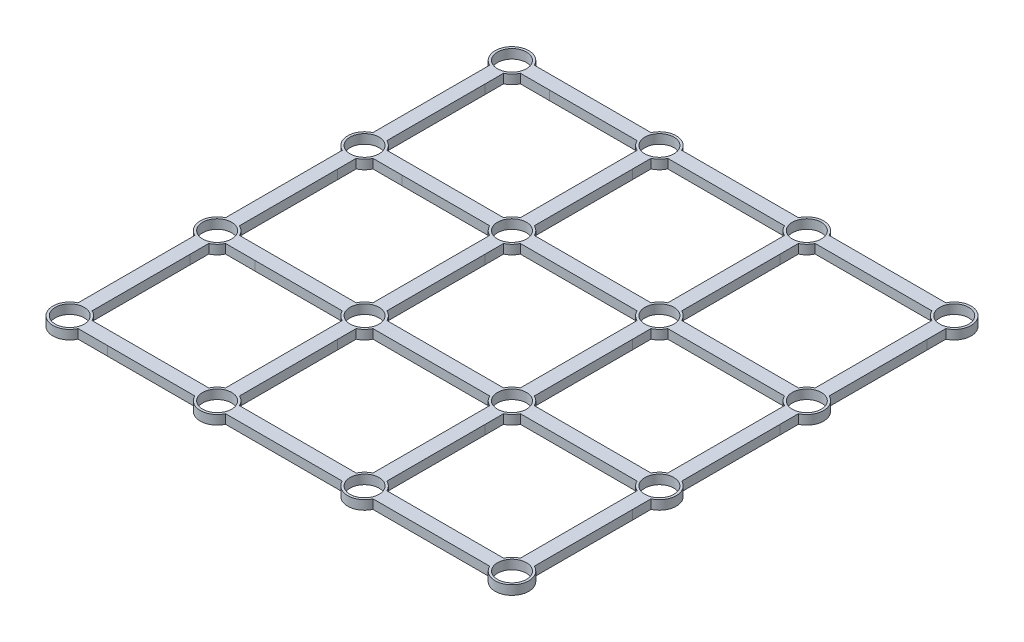
SolidWorks part; units mm, degrees
ref_plane "Front Plane" through (0, 0, 0) normal (0, 0, 1) x (1, 0, 0)
ref_plane "Top Plane" through (0, 0, 0) normal (0, 1, 0) x (1, 0, 0)
ref_plane "Right Plane" through (0, 0, 0) normal (1, 0, 0) x (0, 0, -1)
sketch "Sketch1" plane through (0, 0, 0) normal (0, 1, 0) x (1, 0, 0)
  line L0 (-35.5988, -39.5662) -> (-35.5988, -36.6288) construction
  line L1 (-38.0977, -38.0975) -> (38.1001, -38.0975) construction
  line L2 (-38.0977, -38.0975) -> (-38.098, -10.2001) construction
  line L3 (-15.2963, 38.0999) -> (38.1001, 38.0999) construction
  line L4 (38.1001, -38.0975) -> (38.1001, 38.0999) construction
  line L5 (-38.0977, -38.0975) -> (10.6495, 10.6495) construction
  line L6 (15.3401, -11.5) -> (35.4596, -11.4992)
  line L7 (-10.2, -39.5697) -> (-10.2, -37.3756) construction
  line L8 (15.2, -39.5697) -> (15.2, -39.3) construction
  line L9 (40.6, -39.5697) -> (40.6, -36.6303) construction
  line L10 (-36.8987, -35.9048) -> (-36.8987, -35.9073)
  line L11 (15.2, -14.1697) -> (15.2, -11.2303) construction
  line L12 (40.6, -14.1697) -> (40.6, -11.2303) construction
  line L13 (-10.2, 11.2303) -> (-10.2, 11.2305) construction
  line L14 (15.2, 11.2303) -> (15.2, 11.2305) construction
  line L15 (40.6, 11.2303) -> (40.6, 14.1697) construction
  line L16 (-36.901, 35.9049) -> (-36.901, 35.9064)
  line L17 (15.2, 36.6303) -> (15.2, 36.6305) construction
  line L18 (40.6, 36.6303) -> (40.6, 39.5697) construction
  line L19 (-35.6, -14.1697) -> (-35.6, -11.2303) construction
  line L20 (-35.6, 11.2303) -> (-35.6, 14.1697) construction
  line L21 (-35.6, 36.6303) -> (-35.6, 36.632) construction
  line L22 (-13.9013, 32.2466) -> (-13.8993, 35.4598)
  line L27 (-38.098, -9.7993) -> (-38.0985, 38.0988) construction
  line L28 (40.1506, 40.1506) -> (10.9323, 10.9323) construction
  line L29 (-11.4987, 32.2466) -> (-11.5007, 35.4597)
  line L30 (11.4987, 32.2466) -> (11.5007, 35.4598)
  line L31 (13.9013, 32.2466) -> (13.8993, 35.4598)
  line L32 (-30.4194, 38.0999) -> (-30.4194, 38.8938) construction
  line L37 (-30.4194, 38.0999) -> (-30.4194, 37.3063) construction
  line L38 (-30.4194, 38.0999) -> (-30.4194, 39.3) construction
  line L39 (-30.4194, 38.0999) -> (-30.4194, 36.9) construction
  line L40 (-30.4194, 39.3) -> (-35.4595, 39.2991)
  line L41 (-30.4194, 36.9) -> (-35.4604, 36.901)
  line L42 (-30.4194, 39.3) -> (-15.3399, 39.3)
  line L43 (-30.4194, 36.9) -> (-15.3399, 36.9)
  line L44 (-38.0985, 32.2466) -> (-36.8987, 32.2466) construction
  line L45 (-38.0985, 32.2466) -> (-39.3013, 32.2466) construction
  line L46 (-39.3013, 32.2466) -> (-39.2993, 35.4599)
  line L47 (-36.8987, 32.2466) -> (-36.9007, 35.4606)
  line L48 (-14.8932, 39.2999) -> (-10.5067, 39.3001) construction
  line L49 (-10.0599, 39.3001) -> (10.0599, 39.3001)
  line L50 (-14.8931, 36.9) -> (-10.5069, 36.9) construction
  line L51 (-10.5069, 36.9) -> (-10.5067, 36.9)
  line L52 (10.5069, 36.9) -> (14.8931, 36.9) construction
  line L53 (10.5068, 39.3001) -> (14.8933, 39.3001) construction
  line L55 (15.34, 36.9) -> (35.4597, 36.9)
  line L56 (0, 41) -> (0, -41) construction
  line L57 (-41, 0) -> (41, 0) construction
  line L58 (36.8987, 32.2466) -> (36.8999, 35.4597)
  line L59 (39.3013, 32.2466) -> (39.3003, 35.4598)
  line L60 (-39.3013, 32.2466) -> (-39.3013, 15.3396)
  line L61 (-36.8987, 32.2466) -> (-36.8987, 15.3396)
  line L62 (-13.9013, 32.2466) -> (-13.9013, 15.3397)
  line L63 (-11.4987, 32.2466) -> (-11.4987, 15.3397)
  line L64 (11.4987, 32.2466) -> (11.4987, 15.3397)
  line L65 (13.9013, 32.2466) -> (13.9013, 15.3397)
  line L66 (36.8987, 32.2466) -> (36.8987, 15.3401)
  line L67 (39.3013, 32.2466) -> (39.3013, 15.3401)
  line L68 (-30.4194, 13.9) -> (-35.4595, 13.8991)
  line L69 (-30.4194, 11.5) -> (-35.4596, 11.501)
  line L70 (-30.4194, 11.5) -> (-15.34, 11.5)
  line L71 (-30.4194, 13.9) -> (-15.3401, 13.9)
  line L72 (-10.0598, 13.9001) -> (10.0599, 13.9001)
  line L73 (-10.06, 11.5) -> (10.06, 11.5)
  line L74 (15.3402, 13.9001) -> (35.4593, 13.9001)
  line L75 (15.34, 11.5) -> (35.4591, 11.5)
  line L76 (-30.4194, -11.5) -> (-35.4601, -11.5009)
  line L77 (-30.4194, -13.9) -> (-35.4599, -13.899)
  line L78 (-30.4194, -13.9) -> (-15.3401, -13.9)
  line L79 (-30.4194, -11.5) -> (-15.3401, -11.5)
  line L80 (-10.06, -11.4999) -> (10.06, -11.4999)
  line L81 (-10.0599, -13.9) -> (10.0599, -13.9)
  line L83 (15.3401, -13.9) -> (35.4599, -13.9)
  line L84 (-30.4194, -36.9) -> (-35.4577, -36.9009)
  line L85 (-30.4194, -39.3) -> (-35.4599, -39.299)
  line L86 (-30.4194, -39.3) -> (-15.3404, -39.3)
  line L87 (-30.4194, -36.9) -> (-15.3405, -36.9)
  line L88 (-10.0595, -36.8999) -> (10.0595, -36.8999)
  line L89 (-10.0596, -39.3) -> (10.0597, -39.3)
  line L90 (15.3405, -36.8999) -> (35.4595, -36.8999)
  line L91 (15.3404, -39.3) -> (35.4599, -39.3)
  line L92 (-39.3013, 6.8466) -> (-39.3013, -10.0604)
  line L93 (-36.8987, 6.8466) -> (-36.8987, -10.0609)
  line L94 (-13.9013, 6.8466) -> (-13.9013, -10.0605)
  line L95 (-11.4987, 6.8466) -> (-11.4987, -10.0605)
  line L96 (11.4987, 6.8466) -> (11.4987, -10.0605)
  line L97 (13.9013, 6.8466) -> (13.9013, -10.0605)
  line L98 (36.8987, 6.8466) -> (36.8987, -10.0596)
  line L99 (39.3013, 6.8466) -> (39.3013, -10.0599)
  line L100 (-39.3013, 6.8466) -> (-39.2993, 10.0599)
  line L101 (-36.8987, 6.8466) -> (-36.9007, 10.0599)
  line L102 (-13.9013, 6.8466) -> (-13.8993, 10.0598)
  line L103 (-11.4987, 6.8466) -> (-11.5007, 10.0598)
  line L104 (11.4987, 6.8466) -> (11.5007, 10.0598)
  line L105 (13.9013, 6.8466) -> (13.8993, 10.0598)
  line L106 (36.8987, 6.8466) -> (36.8999, 10.0591)
  line L107 (39.3013, 6.8466) -> (39.3003, 10.0591)
  line L108 (-39.3013, -18.5534) -> (-39.3013, -35.4607)
  line L109 (-36.8987, -18.5534) -> (-36.8987, -35.4586)
  line L110 (-13.9013, -18.5534) -> (-13.9013, -35.4599)
  line L111 (-11.4987, -18.5534) -> (-11.4987, -35.4599)
  line L112 (11.4987, -18.5534) -> (11.4987, -35.4599)
  line L113 (13.9013, -18.5534) -> (13.9013, -35.4599)
  line L114 (36.8987, -18.5534) -> (36.8987, -35.4599)
  line L115 (39.3013, -18.5534) -> (39.3013, -35.4601)
  line L116 (-39.3013, -18.5534) -> (-39.2993, -15.3408)
  line L117 (-36.8987, -18.5534) -> (-36.9007, -15.3403)
  line L118 (-13.9013, -18.5534) -> (-13.8993, -15.3404)
  line L119 (-11.4987, -18.5534) -> (-11.5007, -15.3404)
  line L120 (11.4987, -18.5534) -> (11.5007, -15.3404)
  line L121 (13.9013, -18.5534) -> (13.8993, -15.3404)
  line L122 (36.8987, -18.5534) -> (36.8999, -15.3394)
  line L123 (39.3013, -18.5534) -> (39.3003, -15.339)
  line L124 (15.2, 13.9001) -> (15.2, 14.1697) construction
  line L125 (15.2, -36.8999) -> (15.2, -36.6303) construction
  line L126 (38.0998, -38.0995) -> (-41.0002, 41.0005) construction
  line L128 (-35.9036, -36.901) -> (-35.9061, -36.901)
  line L129 (15.2, 12.6828) -> (15.2, 12.7176) construction
  line L130 (10.9324, 10.9323) -> (38.1001, 38.0999) construction
  line L131 (10.6495, 10.6495) -> (-41, -41) construction
  line L132 (36.9001, 10.5063) -> (36.9001, 10.5067)
  line L133 (35.9064, 11.5) -> (35.9068, 11.5)
  line L134 (36.9001, 35.9063) -> (36.9001, 35.9067)
  line L135 (35.9065, 36.9) -> (35.9068, 36.9)
  line L136 (15.3401, 39.3001) -> (35.4599, 39.3001)
  line L137 (15.2, 38.0823) -> (15.2, 38.1181) construction
  line L138 (-10.0599, 36.9) -> (10.0601, 36.9)
  line L139 (-10.2, 38.0745) -> (-10.2, 38.1257) construction
  line L140 (-35.9047, 36.901) -> (-35.9063, 36.901)
  line L141 (-35.6, 38.0309) -> (-35.6, 38.1666) construction
  arc A0 (-39.3013, -35.4607) -> (-35.4599, -39.299) centre (-38.0977, -38.0975) ccw
  arc A1 (-39.3013, -35.9073) -> (-35.9063, -39.299) centre (-38.0977, -38.0975) ccw
  arc A2 (-15.3404, -39.3) -> (-10.0596, -39.3) centre (-12.7, -38.0998) ccw
  arc A3 (-13.9013, -35.9073) -> (-14.8933, -36.9) centre (-12.7, -38.0998) ccw
  arc A4 (10.0597, -39.3) -> (15.3404, -39.3) centre (12.7, -38.0998) ccw
  arc A5 (11.4987, -35.9073) -> (10.5068, -36.8999) centre (12.7, -38.0998) ccw
  arc A6 (35.4599, -39.3) -> (39.3013, -35.4601) centre (38.0998, -38.0995) ccw
  arc A7 (36.8998, -35.9064) -> (35.9067, -36.8996) centre (38.0998, -38.0995) ccw
  arc A8 (-15.3401, -13.9) -> (-13.8993, -15.3404) centre (-12.7, -12.7) ccw
  arc A9 (-13.9, -10.5068) -> (-14.8932, -11.5) centre (-12.7, -12.7) ccw construction
  arc A10 (11.4987, -10.0605) -> (10.06, -11.4999) centre (12.7, -12.7) ccw
  arc A11 (11.5, -10.5068) -> (10.5068, -11.5) centre (12.7, -12.7) ccw
  arc A12 (39.3003, -15.339) -> (39.3013, -10.0599) centre (38.0997, -12.6992) ccw
  arc A13 (36.8997, -10.5061) -> (35.9065, -11.4992) centre (38.0997, -12.6992) ccw
  arc A14 (-15.34, 11.5) -> (-13.8993, 10.0598) centre (-12.7, 12.7002) ccw
  arc A15 (-13.9013, 14.8927) -> (-14.8933, 13.9) centre (-12.7, 12.7002) ccw construction
  arc A16 (11.4987, 15.3397) -> (10.0599, 13.9001) centre (12.7, 12.7002) ccw
  arc A17 (11.4987, 14.8927) -> (10.5068, 13.9001) centre (12.7, 12.7002) ccw
  arc A18 (36.8987, 15.3401) -> (35.4593, 13.9001) centre (38.1, 12.6998) ccw
  arc A19 (35.9068, 11.5) -> (36.9001, 10.5067) centre (38.1, 12.6998) ccw
  arc A20 (-15.3399, 36.9) -> (-13.8993, 35.4598) centre (-12.6999, 38.1001) ccw
  arc A21 (-14.8931, 36.9) -> (-13.8989, 35.9063) centre (-12.6999, 38.1001) ccw construction
  arc A22 (10.0601, 36.9) -> (11.5007, 35.4598) centre (12.7, 38.1002) ccw
  arc A23 (10.5069, 36.9) -> (11.501, 35.9065) centre (12.7, 38.1002) ccw construction
  arc A24 (35.4597, 36.9) -> (36.8999, 35.4597) centre (38.1, 38.0998) ccw
  arc A25 (35.9068, 36.9) -> (36.9001, 35.9067) centre (38.1, 38.0998) ccw construction
  arc A26 (-39.3013, -10.0604) -> (-39.2993, -15.3408) centre (-38.1005, -12.7001) ccw
  arc A27 (-39.3005, -10.507) -> (-39.3005, -14.8933) centre (-38.1005, -12.7001) ccw
  arc A28 (-39.3013, 15.3396) -> (-39.2993, 10.0599) centre (-38.1, 12.7002) ccw
  arc A29 (-39.3013, 14.8927) -> (-39.299, 10.5065) centre (-38.1, 12.7002) ccw construction
  arc A31 (-35.9061, 39.299) -> (-39.299, 35.9065) centre (-38.1007, 38.1009) ccw construction
  arc A32 (-35.9061, 39.299) -> (-39.299, 35.9065) centre (-38.0985, 38.0988) ccw
  arc A33 (-36.901, 35.9064) -> (-35.9063, 36.901) centre (-38.0985, 38.0988) ccw
  arc A34 (-36.901, 35.9064) -> (-35.9063, 36.901) centre (-38.1007, 38.1009) ccw construction
  arc A35 (-14.8931, 36.9) -> (-13.8989, 35.9063) centre (-12.6999, 38.1001) ccw
  arc A36 (-10.5067, 39.3001) -> (-14.8932, 39.2999) centre (-12.6999, 38.1001) ccw construction
  arc A37 (-10.5067, 39.3001) -> (-14.8932, 39.2999) centre (-12.6999, 38.1001) ccw
  arc A38 (10.5069, 36.9) -> (11.501, 35.9065) centre (12.7, 38.1002) ccw
  arc A39 (14.8933, 39.3001) -> (10.5068, 39.3001) centre (12.7, 38.1002) ccw construction
  arc A40 (14.8933, 39.3001) -> (10.5068, 39.3001) centre (12.7, 38.1002) ccw
  arc A41 (35.9068, 36.9) -> (36.9001, 35.9067) centre (38.1001, 38.0999) ccw
  arc A42 (39.3001, 35.9064) -> (35.9066, 39.3001) centre (38.1, 38.0998) ccw construction
  arc A43 (39.3001, 35.9064) -> (35.9066, 39.3001) centre (38.1001, 38.0999) ccw
  arc A44 (-11.501, 35.9064) -> (-10.5069, 36.9) centre (-12.6999, 38.1001) ccw construction
  arc A45 (-11.501, 35.9064) -> (-10.5069, 36.9) centre (-12.6999, 38.1001) ccw
  arc A46 (13.899, 35.9064) -> (14.8931, 36.9) centre (12.7, 38.1002) ccw construction
  arc A47 (13.899, 35.9064) -> (14.8931, 36.9) centre (12.7, 38.1002) ccw
  arc A48 (-39.3013, 14.8927) -> (-39.299, 10.5065) centre (-38.1, 12.7002) ccw
  arc A49 (-35.9061, 13.899) -> (-36.8987, 14.8927) centre (-38.1, 12.7002) ccw construction
  arc A50 (-35.9061, 13.899) -> (-36.8987, 14.8927) centre (-38.1, 12.7002) ccw
  arc A51 (-36.901, 10.5064) -> (-35.9063, 11.501) centre (-38.1, 12.7002) ccw construction
  arc A52 (-36.901, 10.5064) -> (-35.9063, 11.501) centre (-38.1, 12.7002) ccw
  arc A53 (-13.9013, 14.8927) -> (-14.8933, 13.9) centre (-12.7, 12.7002) ccw
  arc A55 (-14.8931, 11.5) -> (-13.899, 10.5065) centre (-12.7, 12.7002) ccw construction
  arc A56 (-14.8931, 11.5) -> (-13.899, 10.5065) centre (-12.7, 12.7002) ccw
  arc A57 (-11.501, 10.5064) -> (-10.5069, 11.5) centre (-12.7, 12.7002) ccw construction
  arc A58 (-11.501, 10.5064) -> (-10.5069, 11.5) centre (-12.7, 12.7002) ccw
  arc A59 (-10.5067, 13.9001) -> (-11.4987, 14.8927) centre (-12.7, 12.7002) ccw construction
  arc A60 (-10.5067, 13.9001) -> (-11.4987, 14.8927) centre (-12.7, 12.7002) ccw
  arc A61 (10.5069, 11.5) -> (11.501, 10.5065) centre (12.7, 12.7002) ccw
  arc A62 (13.899, 10.5064) -> (14.8931, 11.5) centre (12.7, 12.7002) ccw
  arc A63 (14.8933, 13.9001) -> (13.9013, 14.8927) centre (12.7, 12.7002) ccw
  arc A64 (36.8987, 14.8927) -> (35.9066, 13.9001) centre (38.1, 12.6998) ccw
  arc A65 (39.3001, 10.5064) -> (39.3013, 14.8927) centre (38.1, 12.6998) ccw
  arc A66 (-35.9073, -11.5001) -> (-36.9005, -10.507) centre (-38.1005, -12.7001) ccw
  arc A67 (-36.9005, -14.8933) -> (-35.9073, -13.9001) centre (-38.1005, -12.7001) ccw
  arc A68 (-13.9, -10.5068) -> (-14.8932, -11.5) centre (-12.7, -12.7) ccw
  arc A69 (-14.8932, -13.9) -> (-13.9, -14.8931) centre (-12.7, -12.7) ccw construction
  arc A70 (-14.8932, -13.9) -> (-13.9, -14.8931) centre (-12.7, -12.7) ccw
  arc A71 (-11.5, -14.8931) -> (-10.5068, -13.9) centre (-12.7, -12.7) ccw construction
  arc A72 (-11.5, -14.8931) -> (-10.5068, -13.9) centre (-12.7, -12.7) ccw
  arc A73 (-10.5068, -11.5) -> (-11.5, -10.5068) centre (-12.7, -12.7) ccw construction
  arc A74 (-10.5068, -11.5) -> (-11.5, -10.5068) centre (-12.7, -12.7) ccw
  arc A75 (10.5068, -13.9) -> (11.5, -14.8932) centre (12.7, -12.7) ccw
  arc A76 (14.8932, -11.5) -> (13.9, -10.5068) centre (12.7, -12.7) ccw
  arc A77 (13.9, -14.8932) -> (14.8932, -13.9) centre (12.7, -12.7) ccw
  arc A78 (35.9065, -13.8992) -> (36.8997, -14.8924) centre (38.0997, -12.6992) ccw
  arc A79 (39.2997, -14.8924) -> (39.2997, -10.5061) centre (38.0997, -12.6992) ccw
  arc A80 (-35.9061, -36.901) -> (-36.8987, -35.9073) centre (-38.0977, -38.0975) ccw
  arc A81 (-14.8931, -39.3) -> (-10.5069, -39.3) centre (-12.7, -38.0998) ccw
  arc A82 (-13.9013, -35.4599) -> (-15.3405, -36.9) centre (-12.7, -38.0998) ccw
  arc A83 (-10.5067, -36.8999) -> (-11.4986, -35.9073) centre (-12.7, -38.0998) ccw
  arc A84 (-10.0595, -36.8999) -> (-11.4987, -35.4599) centre (-12.7, -38.0998) ccw
  arc A85 (10.5069, -39.3) -> (14.8931, -39.3) centre (12.7, -38.0998) ccw
  arc A86 (11.4987, -35.4599) -> (10.0595, -36.8999) centre (12.7, -38.0998) ccw
  arc A87 (14.8933, -36.8999) -> (13.9014, -35.9073) centre (12.7, -38.0998) ccw
  arc A88 (15.3405, -36.8999) -> (13.9013, -35.4599) centre (12.7, -38.0998) ccw
  arc A89 (35.9067, -39.2994) -> (39.3014, -35.9073) centre (38.0998, -38.0995) ccw
  arc A90 (-35.4577, -36.9009) -> (-36.8987, -35.4586) centre (-38.0977, -38.0975) ccw
  arc A91 (-36.9007, -15.3403) -> (-35.4599, -13.899) centre (-38.1005, -12.7001) ccw
  arc A92 (-36.9007, 10.0599) -> (-35.4596, 11.501) centre (-38.1, 12.7002) ccw
  arc A93 (-10.0599, 39.3001) -> (-15.3399, 39.3) centre (-12.6999, 38.1001) ccw
  arc A94 (15.3401, 39.3001) -> (10.0599, 39.3001) centre (12.7, 38.1002) ccw
  arc A95 (39.3003, 35.4598) -> (35.4599, 39.3001) centre (38.1, 38.0998) ccw
  arc A96 (39.3003, 10.0591) -> (39.3013, 15.3401) centre (38.1, 12.6998) ccw
  arc A97 (36.8987, -10.0596) -> (35.4596, -11.4992) centre (38.0997, -12.6992) ccw
  arc A98 (36.8987, -35.4599) -> (35.4595, -36.8999) centre (38.0998, -38.0995) ccw
  arc A99 (-39.3005, -10.507) -> (-39.3005, -14.8933) centre (-38.1005, -12.7001) cw
  arc A100 (-35.4601, -11.5009) -> (-36.8987, -10.0609) centre (-38.1005, -12.7001) ccw
  circle A101 centre (-12.7, -12.7) radius 2.5
  circle A102 centre (12.7, -12.7) radius 2.5
  arc A103 (-13.9013, -10.0605) -> (-15.3401, -11.5) centre (-12.7, -12.7) ccw
  arc A104 (-10.06, -11.4999) -> (-11.4987, -10.0605) centre (-12.7, -12.7) ccw
  arc A105 (-11.5007, -15.3404) -> (-10.0599, -13.9) centre (-12.7, -12.7) ccw
  arc A106 (10.0599, -13.9) -> (11.5007, -15.3404) centre (12.7, -12.7) ccw
  arc A107 (13.8993, -15.3404) -> (15.3401, -13.9) centre (12.7, -12.7) ccw
  arc A108 (15.3401, -11.5) -> (13.9013, -10.0605) centre (12.7, -12.7) ccw
  arc A109 (35.4599, -13.9) -> (36.8999, -15.3394) centre (38.0997, -12.6992) ccw
  circle A110 centre (38.0997, -12.6992) radius 2.5
  circle A111 centre (38.1001, -38.0975) radius 2.4978
  circle A112 centre (12.7, -38.0998) radius 2.5
  circle A113 centre (-12.7, -38.0998) radius 2.5
  circle A114 centre (-38.0977, -38.0975) radius 2.4991
  arc A115 (-35.4595, 13.8991) -> (-36.8987, 15.3396) centre (-38.1, 12.7002) ccw
  circle A116 centre (-38.1, 12.7002) radius 2.5
  circle A117 centre (-12.7, 12.7002) radius 2.5
  arc A118 (-13.9013, 15.3397) -> (-15.3401, 13.9) centre (-12.7, 12.7002) ccw
  arc A119 (-10.0598, 13.9001) -> (-11.4987, 15.3397) centre (-12.7, 12.7002) ccw
  arc A120 (-11.5007, 10.0598) -> (-10.06, 11.5) centre (-12.7, 12.7002) ccw
  circle A121 centre (12.7, 12.7002) radius 2.5
  arc A122 (10.06, 11.5) -> (11.5007, 10.0598) centre (12.7, 12.7002) ccw
  arc A123 (13.8993, 10.0598) -> (15.34, 11.5) centre (12.7, 12.7002) ccw
  arc A124 (15.3402, 13.9001) -> (13.9013, 15.3397) centre (12.7, 12.7002) ccw
  circle A125 centre (38.1, 12.6998) radius 2.5003
  arc A126 (35.4591, 11.5) -> (36.8999, 10.0591) centre (38.1, 12.6998) ccw
  circle A127 centre (38.1001, 38.0999) radius 2.5004
  circle A128 centre (12.7, 38.1002) radius 2.5
  arc A129 (13.8993, 35.4598) -> (15.34, 36.9) centre (12.7, 38.1002) ccw
  circle A130 centre (-12.6999, 38.1001) radius 2.5
  arc A131 (-11.5007, 35.4597) -> (-10.0599, 36.9) centre (-12.6999, 38.1001) ccw
  circle A132 centre (-38.0985, 38.0988) radius 2.4995
  arc A133 (-36.9007, 35.4606) -> (-35.4604, 36.901) centre (-38.1007, 38.1009) ccw
  arc A134 (-35.4595, 39.2991) -> (-39.2993, 35.4599) centre (-38.1007, 38.1009) ccw
  point P1 (0, 0)
  point P8 (0, 0)
  point P11 (-35.5988, -38.0975)
  dimension "D3" = 3
  dimension "D4" = 4
  dimension "D5" = 4
  dimension "D6" = 3
extrude "Boss-Extrude2" add sketch "Sketch1" along normal blind 1.5875
